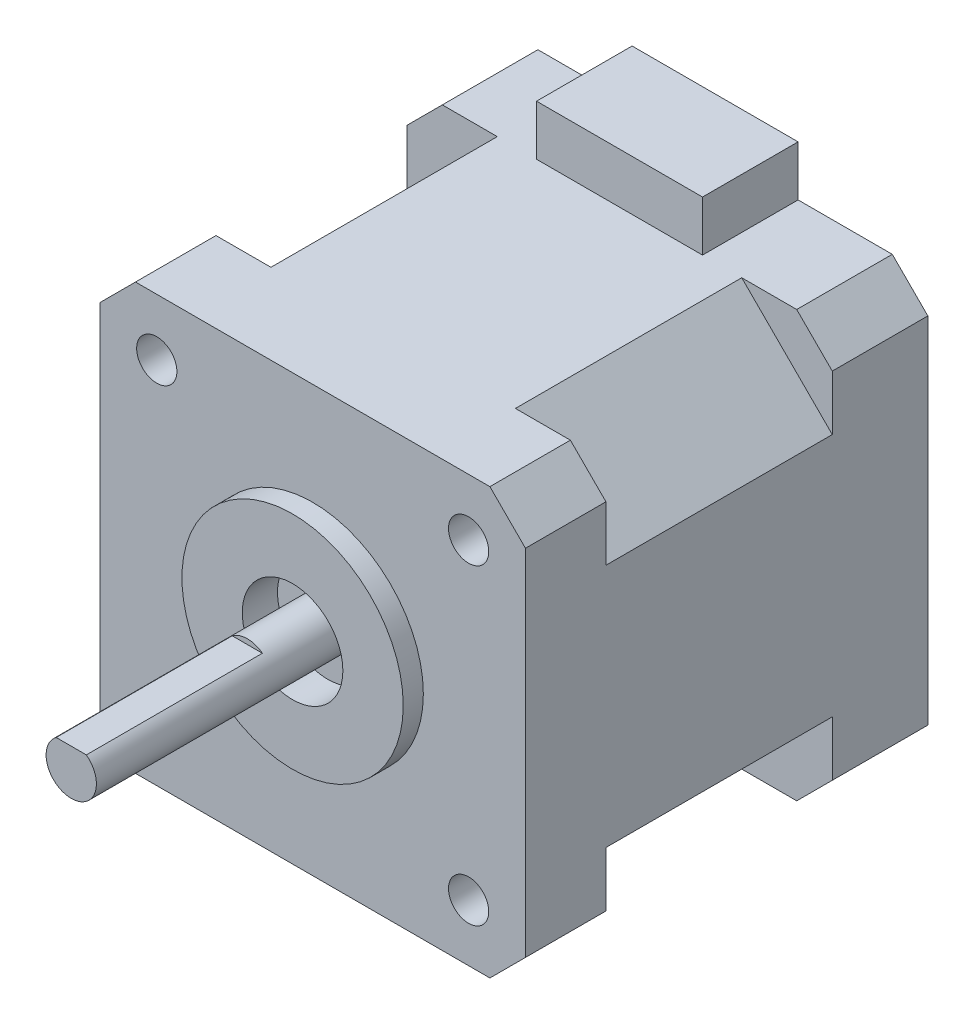
SolidWorks part; units mm, degrees
ref_plane "Alzado" through (0, 0, 0) normal (0, 0, 1) x (1, 0, 0)
ref_plane "Planta" through (0, 0, 0) normal (0, 1, 0) x (1, 0, 0)
ref_plane "Vista lateral" through (0, 0, 0) normal (1, 0, 0) x (0, 0, -1)
sketch "Croquis1" plane through (0, 0, 0) normal (0, 0, 1) x (1, 0, 0)
  line L0 (-17.6145, -21.15) -> (17.6145, -21.15)
  line L1 (17.6145, -21.15) -> (21.15, -17.6145)
  line L2 (21.15, -17.6145) -> (21.15, 17.6145)
  line L3 (21.15, 17.6145) -> (17.6145, 21.15)
  line L4 (17.6145, 21.15) -> (-17.6145, 21.15)
  line L5 (-17.6145, 21.15) -> (-21.15, 17.6145)
  line L6 (-21.15, 17.6145) -> (-21.15, -17.6145)
  line L7 (-21.15, -17.6145) -> (-17.6145, -21.15)
  point P2 (0, 0)
  dimension "D1" = 21.15
  dimension "D2" = 21.15
  dimension "D3" = 42.3
  dimension "D4" = 42.3
  dimension "D5" = 5
  dimension "D6" = 135
extrude "Saliente-Extruir1" add sketch "Croquis1" against normal blind 40 contours L6 L7 L0 L1 L2 L3 L4 L5
sketch "Croquis2" plane through (0, 0, 0) normal (0, 0, 1) x (1, 0, 0)
  circle A0 centre (0, 0) radius 11
  dimension "D1" = 22
extrude "Saliente-Extruir2" add sketch "Croquis2" along normal blind 2
sketch "Croquis3" plane through (0, 0, 2) normal (0, 0, 1) x (1, 0, 0)
  circle A0 centre (0, 0) radius 5
  dimension "D1" = 10
extrude "Cortar-Extruir1" cut sketch "Croquis3" against normal blind 3.5
sketch "Croquis4" plane through (0, 0, -1.5) normal (0, 0, 1) x (1, 0, 0)
  circle A0 centre (0, 0) radius 2.5
  dimension "D1" = 5
extrude "Saliente-Extruir3" add sketch "Croquis4" along normal blind 25.5
sketch "Croquis5" plane through (0, 0, 0) normal (0, 0, 1) x (1, 0, 0)
  line L1 (15.5, -15.5) -> (-15.5, -15.5) construction
  line L2 (15.5, -15.5) -> (15.5, 15.5) construction
  line L3 (15.5, 15.5) -> (-15.5, 15.5) construction
  line L4 (-15.5, -15.5) -> (-15.5, 15.5) construction
  line L5 (15.5, -15.5) -> (-15.5, 15.5) construction
  line L6 (15.5, 15.5) -> (-15.5, -15.5) construction
  circle A0 centre (-15.5, 15.5) radius 2
  circle A1 centre (15.5, 15.5) radius 2
  circle A2 centre (15.5, -15.5) radius 2
  circle A3 centre (-15.5, -15.5) radius 2
  point P0 (0, 0)
  dimension "D3" = 4
  dimension "D1" = 31
  dimension "D2" = 31
extrude "Cortar-Extruir2" cut sketch "Croquis5" against normal blind 4.5
sketch "Croquis6" plane through (0, 0, 24) normal (0, 0, 1) x (1, 0, 0)
  line L0 (-1.5, 2) -> (1.5, 2)
  arc A0 (1.5, 2) -> (-1.5, 2) centre (0, 0) ccw
  circle A1 centre (0, 0) radius 2.5 construction
  dimension "D1" = 2
extrude "Cortar-Extruir3" cut sketch "Croquis6" against normal blind 17.5
sketch "Croquis7" plane through (0, 0, 0) normal (0, 0, 1) x (1, 0, 0)
  line L0 (-21.15, 12.15) -> (-12.15, 21.15)
  line L1 (-21.15, 17.6145) -> (-21.15, -17.6145) construction
  line L2 (17.6145, 21.15) -> (-17.6145, 21.15) construction
  line L3 (-12.15, 21.15) -> (-21.15, 21.15)
  line L4 (-21.15, 21.15) -> (-21.15, 12.15)
  line L5 (0, 21.15) -> (0, -21.15) construction
  line L6 (-17.6145, -21.15) -> (17.6145, -21.15) construction
  line L7 (-21.15, 0) -> (21.15, 0) construction
  line L8 (21.15, -17.6145) -> (21.15, 17.6145) construction
  line L9 (21.15, 21.15) -> (21.15, 12.15)
  line L10 (12.15, 21.15) -> (21.15, 21.15)
  line L11 (21.15, 12.15) -> (12.15, 21.15)
  line L12 (21.15, -21.15) -> (21.15, -12.15)
  line L13 (21.15, -12.15) -> (12.15, -21.15)
  line L14 (12.15, -21.15) -> (21.15, -21.15)
  line L15 (-21.15, -12.15) -> (-12.15, -21.15)
  line L16 (-21.15, -21.15) -> (-21.15, -12.15)
  line L17 (-12.15, -21.15) -> (-21.15, -21.15)
  dimension "D1" = 45
  dimension "D2" = 9
extrude "Cortar-Extruir4" cut sketch "Croquis7" against normal blind 22.5 from offset 8 offset against normal yes
sketch "Croquis8" plane through (0, 21.15, 0) normal (0, 1, 0) x (1, 0, 0)
  line L0 (17.6145, 40) -> (-17.6145, 40) construction
  line L1 (-8.25, 40) -> (8.25, 40)
  line L2 (-8.25, 40) -> (-8.25, 30.5)
  line L3 (-8.25, 30.5) -> (8.25, 30.5)
  line L4 (8.25, 40) -> (8.25, 30.5)
  line L5 (-12.15, 30.5) -> (-17.6145, 30.5) construction
  line L6 (-8.25, 40) -> (-21.15, 40) construction
  line L7 (8.25, 40) -> (21.15, 40) construction
  dimension "D1" = 16.5
extrude "Saliente-Extruir4" add sketch "Croquis8" along normal blind 5
